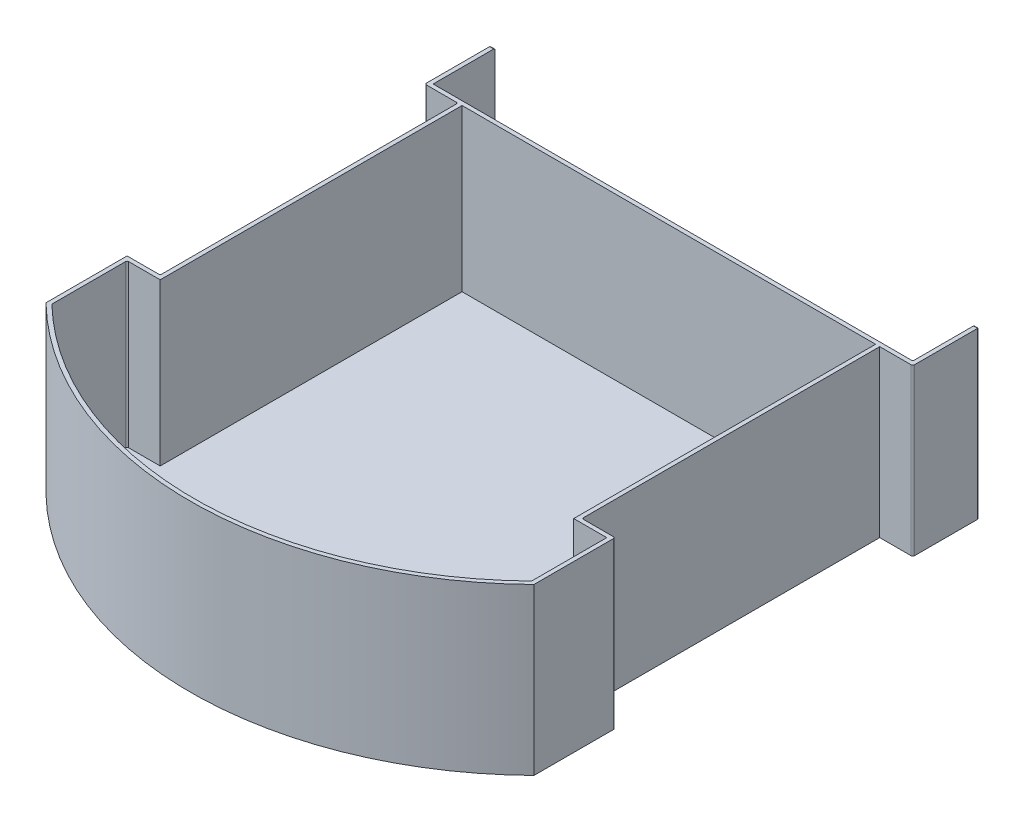
SolidWorks part; units mm, degrees
ref_plane "Front Plane" through (0, 0, 0) normal (0, 0, 1) x (1, 0, 0)
ref_plane "Top Plane" through (0, 0, 0) normal (0, 1, 0) x (1, 0, 0)
ref_plane "Right Plane" through (0, 0, 0) normal (1, 0, 0) x (0, 0, -1)
sketch "Sketch1" plane through (0, 0, 0) normal (0, 1, 0) x (1, 0, 0)
  line L0 (0, 320.6396) -> (0, -352.9607) construction
  line L1 (0, 0) -> (0, -151.2347) construction
  line L2 (-147.5, 118.7653) -> (-145, 118.7653)
  line L3 (147.5, -150.2647) -> (147.5, -101.2347)
  line L4 (-145, 81.2653) -> (-145, 118.7653)
  line L5 (147.5, -101.2347) -> (127.5, -101.2347)
  line L6 (127.5, -101.2347) -> (127.5, 78.7653)
  line L7 (127.5, 78.7653) -> (147.5, 78.7653)
  line L8 (147.5, 78.7653) -> (147.5, 118.7653)
  line L9 (145, -149.2119) -> (145, -103.7347)
  line L10 (145, -103.7347) -> (125, -103.7347)
  line L11 (125, -103.7347) -> (125, 78.7653)
  line L12 (125, 81.2653) -> (145, 81.2653)
  line L13 (145, 81.2653) -> (145, 118.7653)
  line L14 (147.5, 118.7653) -> (145, 118.7653)
  line L15 (145, -151.2347) -> (145, -103.7347) construction
  line L16 (147.5, -151.2347) -> (147.5, -101.2347) construction
  line L17 (-125, 81.2653) -> (-145, 81.2653)
  line L18 (-125, -103.7347) -> (-125, 78.7653)
  line L19 (-145, -103.7347) -> (-125, -103.7347)
  line L20 (-145, -149.2119) -> (-145, -103.7347)
  line L21 (-147.5, 78.7653) -> (-147.5, 118.7653)
  line L22 (-127.5, 78.7653) -> (-147.5, 78.7653)
  line L23 (-127.5, -101.2347) -> (-127.5, 78.7653)
  line L24 (-147.5, -101.2347) -> (-127.5, -101.2347)
  line L25 (-147.5, -150.2647) -> (-147.5, -101.2347)
  line L26 (125, 81.2653) -> (-125, 81.2653)
  line L28 (-125, 78.7653) -> (125, 78.7653)
  line L29 (125, -103.7347) -> (125, 81.2653) construction
  arc A0 (-147.5, -150.2647) -> (147.5, -150.2647) centre (0, 0) ccw
  arc A1 (-145, -149.2119) -> (145, -149.2119) centre (0, 0) ccw
  arc A2 (0, -208.0605) -> (146.551, -147.6888) centre (0, 0) ccw construction
  arc A3 (0, -210.5605) -> (148.3119, -149.4634) centre (0, 0) ccw construction
  dimension "D1" = 2.5
extrude "Boss-Extrude1" add sketch "Sketch1" along normal blind 100
fillet "Fillet1" radius 1 16 edges at (147.5, 50, -118.7653) (146.25, 100, -118.7653) (145, 50, -118.7653) (146.25, 0, -118.7653) (-147.5, 50, 150.2647) (-145, 50, 103.7347) (-127.5, 50, 101.2347) (-127.5, 50, -78.7653) (-147.5, 50, -78.7653) (-146.25, 0, -118.7653) (-146.25, 100, -118.7653) (127.5, 50, 101.2347) (145, 50, 149.2119) (147.5, 50, 101.2347) (145, 50, -81.2653) (147.5, 50, -78.7653)
sketch "Sketch4" plane through (0, 0, 0) normal (0, 1, 0) x (1, 0, 0)
  line L15 (147.5, 79.7653) -> (147.5, 117.7653)
  line L16 (147.5, 117.7653) -> (145, 117.7653)
  line L17 (145, 117.7653) -> (145, 82.2653)
  line L18 (144, 81.2653) -> (-145, 81.2653)
  line L19 (-145, 81.2653) -> (-145, 117.7653)
  line L20 (-145, 117.7653) -> (-147.5, 117.7653)
  line L21 (-147.5, 117.7653) -> (-147.5, 79.7653)
  line L22 (-146.5, 78.7653) -> (-128.5, 78.7653)
  line L23 (-127.5, 77.7653) -> (-127.5, -100.2347)
  line L24 (-128.5, -101.2347) -> (-147.5, -101.2347)
  line L25 (-147.5, -101.2347) -> (-147.5, -149.8444)
  line L26 (147.5, -150.2647) -> (147.5, -102.2347)
  line L27 (146.5, -101.2347) -> (128.5, -101.2347)
  line L28 (127.5, -100.2347) -> (127.5, 78.7653)
  line L29 (127.5, 78.7653) -> (146.5, 78.7653)
  line L30 (147.5, 79.7653) -> (147.5, 117.7653)
  line L31 (147.5, 117.7653) -> (145, 117.7653)
  line L32 (145, 117.7653) -> (145, 82.2653)
  line L33 (144, 81.2653) -> (-145, 81.2653)
  line L34 (-145, 81.2653) -> (-145, 117.7653)
  line L35 (-145, 117.7653) -> (-147.5, 117.7653)
  line L36 (-147.5, 117.7653) -> (-147.5, 79.7653)
  line L37 (-146.5, 78.7653) -> (-128.5, 78.7653)
  line L38 (-127.5, 77.7653) -> (-127.5, -100.2347)
  line L39 (-128.5, -101.2347) -> (-147.5, -101.2347)
  line L40 (-147.5, -101.2347) -> (-147.5, -149.8444)
  line L41 (147.5, -150.2647) -> (147.5, -102.2347)
  line L42 (146.5, -101.2347) -> (128.5, -101.2347)
  line L43 (127.5, -100.2347) -> (127.5, 78.7653)
  line L44 (127.5, 78.7653) -> (146.5, 78.7653)
  arc A9 (144, 81.2653) -> (145, 82.2653) centre (144, 82.2653) ccw
  arc A10 (-147.5, 79.7653) -> (-146.5, 78.7653) centre (-146.5, 79.7653) ccw
  arc A11 (-127.5, 77.7653) -> (-128.5, 78.7653) centre (-128.5, 77.7653) ccw
  arc A12 (-128.5, -101.2347) -> (-127.5, -100.2347) centre (-128.5, -100.2347) ccw
  arc A13 (-147.5, -149.8444) -> (-147.1991, -150.5595) centre (-146.5, -149.8444) ccw
  arc A14 (-147.1991, -150.5595) -> (147.5, -150.2647) centre (0, 0) ccw
  arc A15 (147.5, -102.2347) -> (146.5, -101.2347) centre (146.5, -102.2347) ccw
  arc A16 (127.5, -100.2347) -> (128.5, -101.2347) centre (128.5, -100.2347) ccw
  arc A17 (146.5, 78.7653) -> (147.5, 79.7653) centre (146.5, 79.7653) ccw
  arc A18 (144, 81.2653) -> (145, 82.2653) centre (144, 82.2653) ccw
  arc A19 (-147.5, 79.7653) -> (-146.5, 78.7653) centre (-146.5, 79.7653) ccw
  arc A20 (-127.5, 77.7653) -> (-128.5, 78.7653) centre (-128.5, 77.7653) ccw
  arc A21 (-128.5, -101.2347) -> (-127.5, -100.2347) centre (-128.5, -100.2347) ccw
  arc A22 (-147.5, -149.8444) -> (-147.1991, -150.5595) centre (-146.5, -149.8444) ccw
  arc A23 (-147.1991, -150.5595) -> (147.5, -150.2647) centre (0, 0) ccw
  arc A24 (147.5, -102.2347) -> (146.5, -101.2347) centre (146.5, -102.2347) ccw
  arc A25 (127.5, -100.2347) -> (128.5, -101.2347) centre (128.5, -100.2347) ccw
  arc A26 (146.5, 78.7653) -> (147.5, 79.7653) centre (146.5, 79.7653) ccw
  dimension "D1" = 0
extrude "Boss-Extrude2" add sketch "Sketch4" along normal blind 2.5
sketch "Sketch5" plane through (0, 0, 0) normal (0, 1, 0) x (1, 0, 0)
  line L0 (-125, -103.7347) -> (125, -103.7347) construction
  line L1 (125, -103.7347) -> (125, 75.9096) construction
  line L2 (125, 75.9096) -> (125, 19.1841) construction
  line L3 (125, 19.1841) -> (125, -25.745) construction
  line L4 (-125, 78.7653) -> (-125, 27.6966) construction
  line L5 (-125, 78.7653) -> (-125, -103.7347) construction
  line L6 (-125, 27.6966) -> (-65, 27.6966) construction
  line L7 (-65, 27.6966) -> (-65, 78.7653) construction
  line L8 (125, 78.7653) -> (-125, 78.7653) construction
  line L9 (-65, 78.7653) -> (-5, 78.7653) construction
  line L10 (-5, 78.7653) -> (-5, 27.6966) construction
  line L11 (-5, 27.6966) -> (-65, 27.6966) construction
  line L12 (-125, 27.6966) -> (-125, -39.9098) construction
  line L13 (-125, 78.7653) -> (-125, -103.7347) construction
  line L14 (-125, -39.9098) -> (-65, -39.9098) construction
  line L15 (-65, -39.9098) -> (-65, 27.6966) construction
  line L16 (-125, -39.9098) -> (-125, -99.9098) construction
  line L17 (-125, -99.9098) -> (-65, -99.9098) construction
  line L18 (-65, -99.9098) -> (-65, -39.9098) construction
  line L19 (-65, -39.9098) -> (-5, -39.9098) construction
  line L20 (-5, -39.9098) -> (-5, 27.6966) construction
  line L21 (-5, 27.6966) -> (-5, 78.7653) construction
  line L22 (-5, 78.7653) -> (-5, -99.9098) construction
  line L23 (-5, -99.9098) -> (-65, -99.9098) construction
  line L24 (-65, -99.9098) -> (125, -99.9098) construction
  line L25 (125, -99.9098) -> (125, -39.9098) construction
  line L26 (125, -39.9098) -> (-5, -39.9098) construction
  line L27 (-5, -39.9098) -> (-5, 27.6966) construction
  line L28 (-5, 27.6966) -> (125, 27.6966) construction
  line L29 (125, 27.6966) -> (60, 27.6966) construction
  line L30 (60, 27.6966) -> (60, -99.9098) construction
  line L31 (60, -99.9098) -> (60, 78.7653) construction
  line L32 (125, 78.7653) -> (-125, 78.7653) construction
